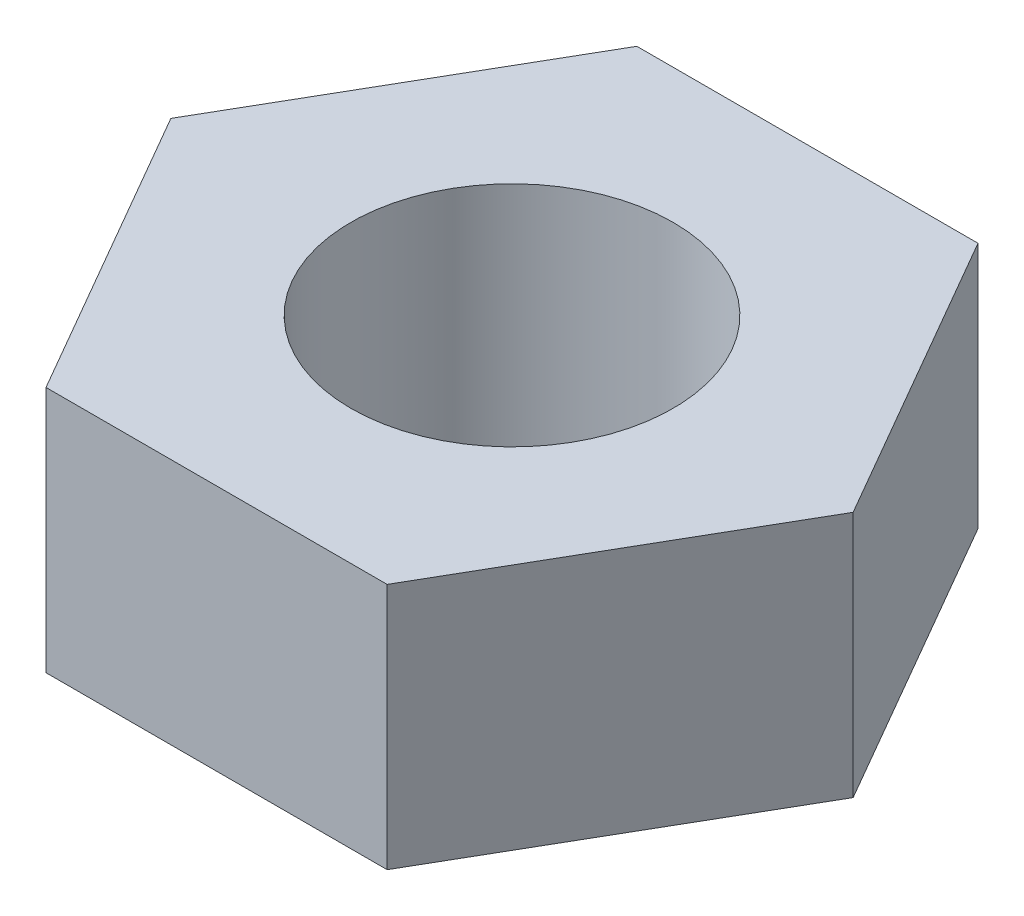
SolidWorks part; units mm, degrees
ref_plane "Front Plane" through (0, 0, 0) normal (0, 0, 1) x (1, 0, 0)
ref_plane "Top Plane" through (0, 0, 0) normal (0, 1, 0) x (1, 0, 0)
ref_plane "Right Plane" through (0, 0, 0) normal (1, 0, 0) x (0, 0, -1)
sketch "Sketch1" plane through (0, 0, 0) normal (0, 1, 0) x (1, 0, 0)
  line L1 (3.1754, 0) -> (1.5877, 2.75)
  line L2 (1.5877, 2.75) -> (-1.5877, 2.75)
  line L3 (-1.5877, 2.75) -> (-3.1754, 0)
  line L4 (-3.1754, 0) -> (-1.5877, -2.75)
  line L5 (-1.5877, -2.75) -> (1.5877, -2.75)
  line L6 (1.5877, -2.75) -> (3.1754, 0)
  circle A0 centre (0, 0) radius 2.75 construction
  circle A1 centre (0, 0) radius 1.5
  dimension "D2" = 3
  dimension "D1" = 5.5
extrude "Boss-Extrude1" add sketch "Sketch1" along normal blind 2.3
